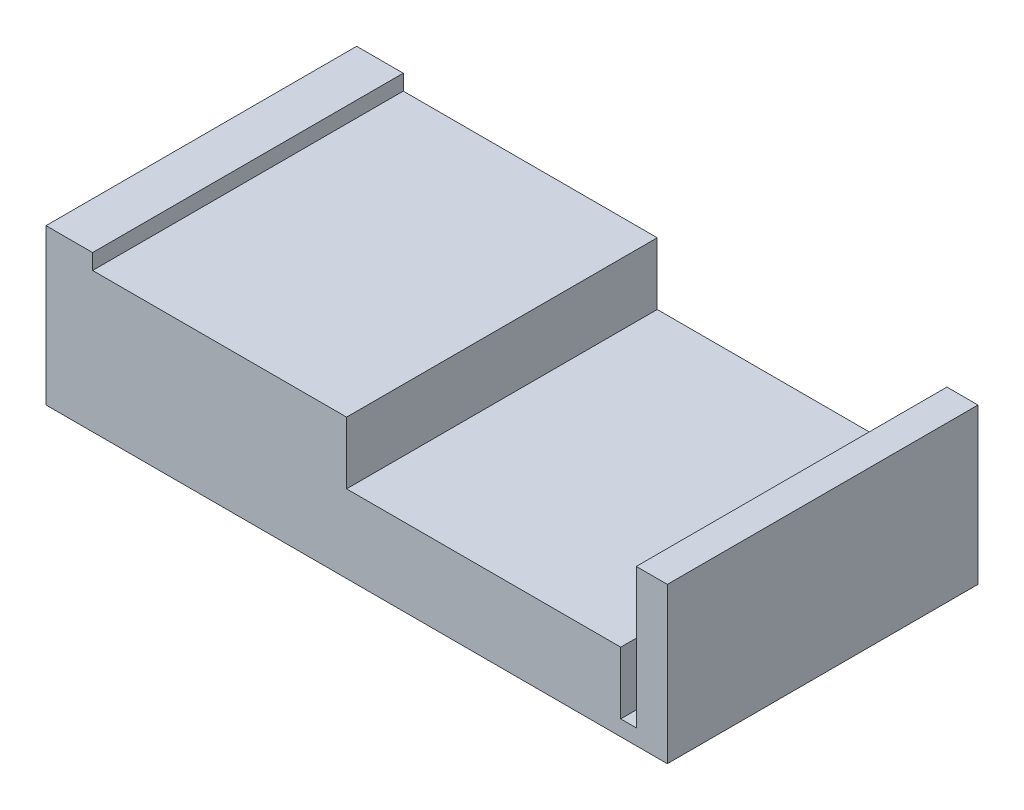
SolidWorks part; units mm, degrees
ref_plane "前视基准面" through (0, 0, 0) normal (0, 0, 1) x (1, 0, 0)
ref_plane "上视基准面" through (0, 0, 0) normal (0, 1, 0) x (1, 0, 0)
ref_plane "右视基准面" through (0, 0, 0) normal (1, 0, 0) x (0, 0, -1)
other "Configuration Table"
sketch "草图1" plane through (0, 0, 0) normal (0, 1, 0) x (1, 0, 0)
  line L1 (0, 0) -> (200, 0)
  line L2 (0, 0) -> (0, 100)
  line L3 (0, 100) -> (200, 100)
  line L4 (200, 0) -> (200, 100)
  dimension "D1" = 100
  dimension "D2" = 200
extrude "凸台-拉伸1" add sketch "草图1" along normal blind 50
sketch "草图2" plane through (0, 50, 0) normal (0, 1, 0) x (1, 0, 0)
  line L0 (200, 100) -> (0, 100) construction
  line L1 (15, 100) -> (96.7527, 100)
  line L2 (15, 100) -> (15, 0)
  line L3 (15, 0) -> (96.7527, 0)
  line L4 (96.7527, 100) -> (96.7527, 0)
  line L5 (0, 100) -> (0, 0) construction
  dimension "D1" = 15
extrude "切除-拉伸1" cut sketch "草图2" against normal blind 5
sketch "草图3" plane through (0, 50, 0) normal (0, 1, 0) x (1, 0, 0)
  line L0 (96.7527, 0) -> (200, 0) construction
  line L1 (96.7527, 100) -> (190, 100)
  line L2 (96.7527, 100) -> (96.7527, 0)
  line L3 (96.7527, 0) -> (190, 0)
  line L4 (190, 100) -> (190, 0)
  line L5 (200, 0) -> (200, 100) construction
  dimension "D1" = 10
extrude "切除-拉伸2" cut sketch "草图3" against normal blind 25
sketch "草图4" plane through (0, 25, 0) normal (0, 1, 0) x (1, 0, 0)
  line L0 (96.7527, 0) -> (190, 0) construction
  line L1 (190, 100) -> (185, 100)
  line L2 (190, 100) -> (190, 0)
  line L3 (190, 0) -> (185, 0)
  line L4 (185, 100) -> (185, 0)
  dimension "D1" = 5
extrude "切除-拉伸3" cut sketch "草图4" against normal blind 20
